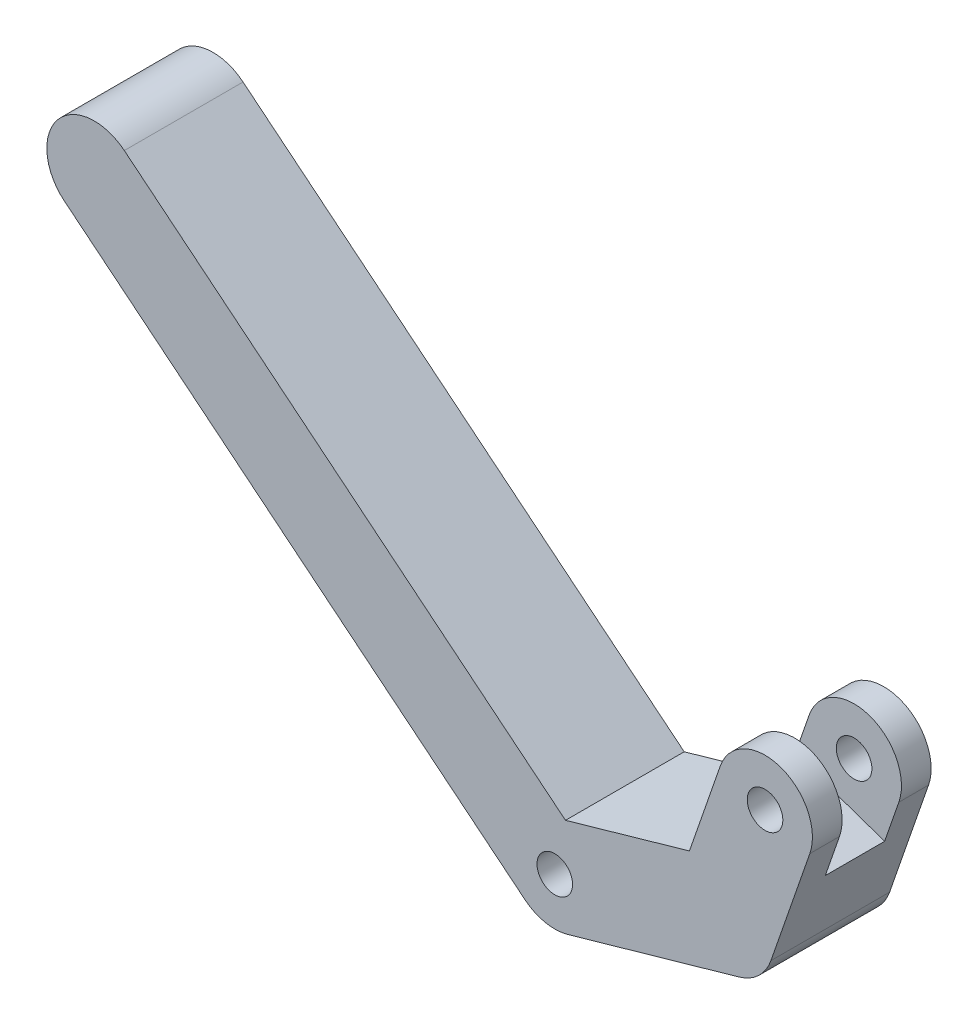
SolidWorks part; units mm, degrees
material "PUR"
ref_plane "Ön Düzlem" through (0, 0, 0) normal (0, 0, 1) x (1, 0, 0)
ref_plane "Üst Düzlem" through (0, 0, 0) normal (0, 1, 0) x (1, 0, 0)
ref_plane "Sağ Düzlem" through (0, 0, 0) normal (1, 0, 0) x (0, 0, -1)
sketch "Çizim1" plane through (0, 0, 0) normal (0, 0, 1) x (1, 0, 0)
  line L0 (0, 0) -> (-38.7838, 31.5565) construction
  line L1 (0, 26.1868) -> (0, -26.1617) construction
  line L2 (0, 0) -> (14.4285, 4.1009) construction
  line L3 (14.4285, 4.1009) -> (17.7062, 13.5485) construction
  line L4 (-41.3083, 28.4538) -> (-2.5245, -3.1027)
  line L5 (1.0959, -3.8469) -> (15.5219, 0.2627)
  line L6 (18.199, 2.7928) -> (21.4767, 12.2404)
  line L7 (-36.2572, 34.6576) -> (0.9005, 4.3827)
  line L8 (13.9358, 14.8566) -> (11.3376, 7.3679)
  line L9 (11.3376, 7.3679) -> (0.9005, 4.3827)
  arc A0 (-36.2572, 34.6576) -> (-41.3083, 28.4538) centre (-38.7838, 31.5565) ccw
  arc A1 (-2.5245, -3.1027) -> (1.0959, -3.8469) centre (0, 0) ccw
  arc A2 (15.5219, 0.2627) -> (18.199, 2.7928) centre (14.4285, 4.1009) ccw
  arc A3 (21.4767, 12.2404) -> (13.9358, 14.8566) centre (17.7062, 13.5485) ccw
  dimension "D6" = 8
  dimension "D7" = 4
  dimension "D1" = 50
  dimension "D2" = 15
  dimension "D3" = 125
  dimension "D4" = 125
  dimension "D5" = 10
extrude "Yükseklik-Ekstrüzyon1" add sketch "Çizim1" along normal mid plane 10
sketch "Çizim2" plane through (0, 0, 5) normal (0, 0, 1) x (1, 0, 0)
  circle A0 centre (17.7062, 13.5485) radius 1.5
  circle A1 centre (0, 0) radius 1.5
  dimension "D1" = 3
extrude "Kes-Ekstrüzyon1" cut sketch "Çizim2" against normal blind 15
sketch "Çizim3" plane through (0, 0, 0) normal (0, 0, 1) x (1, 0, 0)
  line L0 (12.7394, 11.4082) -> (20.2803, 8.792)
  line L6 (11.3376, 7.3679) -> (0.9005, 4.3827)
  line L7 (0.9005, 4.3827) -> (-36.2572, 34.6576)
  line L8 (-41.3083, 28.4538) -> (-2.5245, -3.1027)
  line L9 (1.0959, -3.8469) -> (15.5219, 0.2627)
  line L10 (18.199, 2.7928) -> (21.4767, 12.2404)
  line L11 (13.9358, 14.8566) -> (11.3376, 7.3679)
  line L16 (20.2803, 8.792) -> (21.4767, 12.2404)
  line L17 (13.9358, 14.8566) -> (12.7394, 11.4082)
  arc A4 (-36.2572, 34.6576) -> (-41.3083, 28.4538) centre (-38.7838, 31.5565) ccw
  arc A5 (-2.5245, -3.1027) -> (1.0959, -3.8469) centre (0, 0) ccw
  arc A6 (15.5219, 0.2627) -> (18.199, 2.7928) centre (14.4285, 4.1009) ccw
  arc A7 (21.4767, 12.2404) -> (13.9358, 14.8566) centre (17.7062, 13.5485) ccw
  arc A11 (21.4767, 12.2404) -> (13.9358, 14.8566) centre (17.7062, 13.5485) ccw
  dimension "D1" = 0
extrude "Kes-Ekstrüzyon2" cut sketch "Çizim3" against normal mid plane 5
